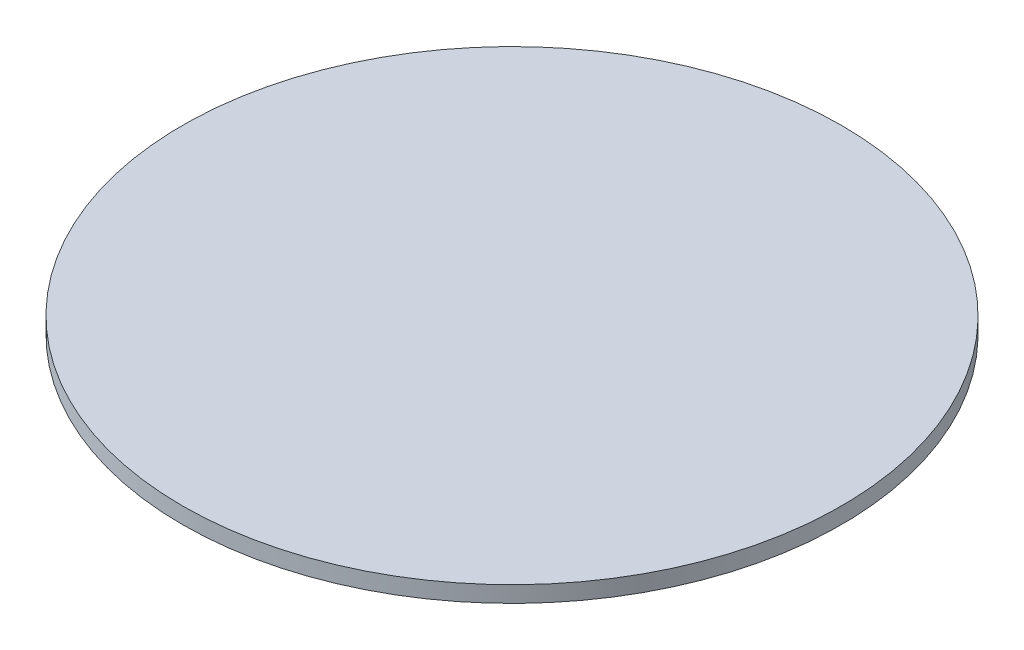
SolidWorks part; units mm, degrees
ref_plane "Front Plane" through (0, 0, 0) normal (0, 0, 1) x (1, 0, 0)
ref_plane "Top Plane" through (0, 0, 0) normal (0, 1, 0) x (1, 0, 0)
ref_plane "Right Plane" through (0, 0, 0) normal (1, 0, 0) x (0, 0, -1)
sketch "Sketch1" plane through (0, 0, 0) normal (0, 1, 0) x (1, 0, 0)
  circle A0 centre (0, 0) radius 32.5
  dimension "D1" = 65
extrude "Boss-Extrude1" add sketch "Sketch1" along normal blind 1.6
